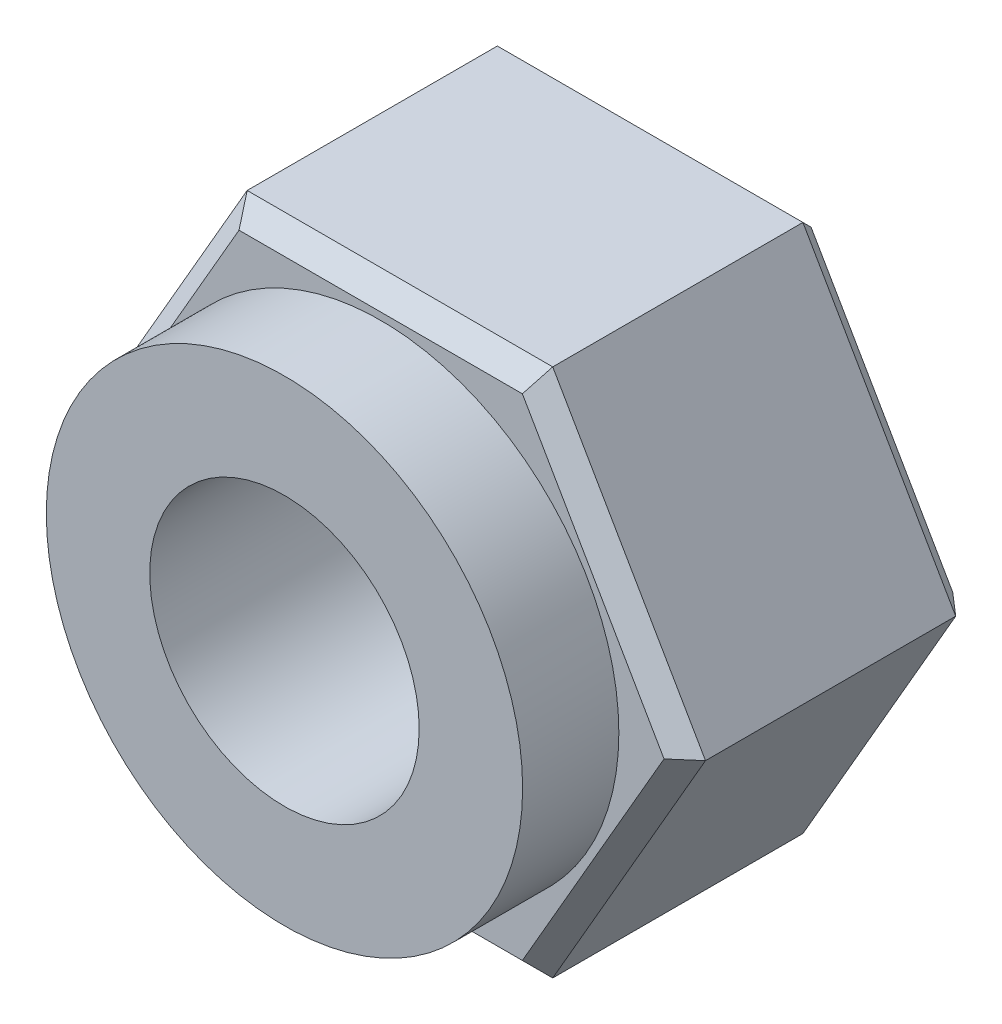
SolidWorks part; units mm, degrees
ref_plane "Front Plane" through (0, 0, 0) normal (0, 0, 1) x (1, 0, 0)
ref_plane "Top Plane" through (0, 0, 0) normal (0, 1, 0) x (1, 0, 0)
ref_plane "Right Plane" through (0, 0, 0) normal (1, 0, 0) x (0, 0, -1)
sketch "Nut Hex Sketch" plane through (0, 0, 0) normal (0, 0, 1) x (1, 0, 0)
  line L1 (3.1754, 0) -> (1.5877, 2.75)
  line L2 (1.5877, 2.75) -> (-1.5877, 2.75)
  line L3 (-1.5877, 2.75) -> (-3.1754, 0)
  line L4 (-3.1754, 0) -> (-1.5877, -2.75)
  line L5 (-1.5877, -2.75) -> (1.5877, -2.75)
  line L6 (1.5877, -2.75) -> (3.1754, 0)
  circle A0 centre (0, 0) radius 2.75 construction
  dimension "D1" = 5.5
extrude "Nut Hex Extrude" add sketch "Nut Hex Sketch" along normal blind 3
chamfer "Hex Edge Chamfers" distance 0.2 12 edges at (2.3816, -1.375, 0) (2.3816, 1.375, 0) (0, 2.75, 0) (-2.3816, 1.375, 0) (-2.3816, -1.375, 0) (0, -2.75, 0) (2.3816, -1.375, 3) (2.3816, 1.375, 3) (0, 2.75, 3) (-2.3816, 1.375, 3) (-2.3816, -1.375, 3) (0, -2.75, 3)
ref_plane "Collar Seat Plane" through (0, 0, 3) normal (0, 0, 1) x (1, 0, 0)
sketch "Nylon Collar Sketch" plane through (0, 0, 3) normal (0, 0, 1) x (1, 0, 0)
  circle A0 centre (0, 0) radius 2.475
  dimension "D1" = 4.95
extrude "Nylon Collar" add sketch "Nylon Collar Sketch" along normal blind 1
sketch "Thread Bore Sketch" plane through (0, 0, 0) normal (0, 0, 1) x (1, 0, 0)
  circle A0 centre (0, 0) radius 1.4
  dimension "D1" = 2.8
extrude "Thread Bore Cut" cut sketch "Thread Bore Sketch" along normal through all
equation "\"nut_across_flats\"= 5.5mm 'M3 nut hex across flats"
equation "\"nut_height\"= 3mm 'Metal hex height"
equation "\"thread_bore_diameter\"= 2.8mm 'Simplified thread bore"
equation "\"edge_break\"= 0.2mm 'Native edge break on hex perimeter"
equation "\"collar_diameter\"= 4.95mm 'Nylon collar outside diameter"
equation "\"collar_height\"= 1mm 'Nylon collar axial height"
equation "\"D1@Nut Hex Sketch\"= \"nut_across_flats\""
equation "\"D1@Nut Hex Extrude\"= \"nut_height\""
equation "\"D1@Hex Edge Chamfers\"= \"edge_break\""
equation "\"D1@Collar Seat Plane\"= \"nut_height\""
equation "\"D1@Nylon Collar Sketch\"= \"collar_diameter\""
equation "\"D1@Nylon Collar\"= \"collar_height\""
equation "\"D1@Thread Bore Sketch\"= \"thread_bore_diameter\""
